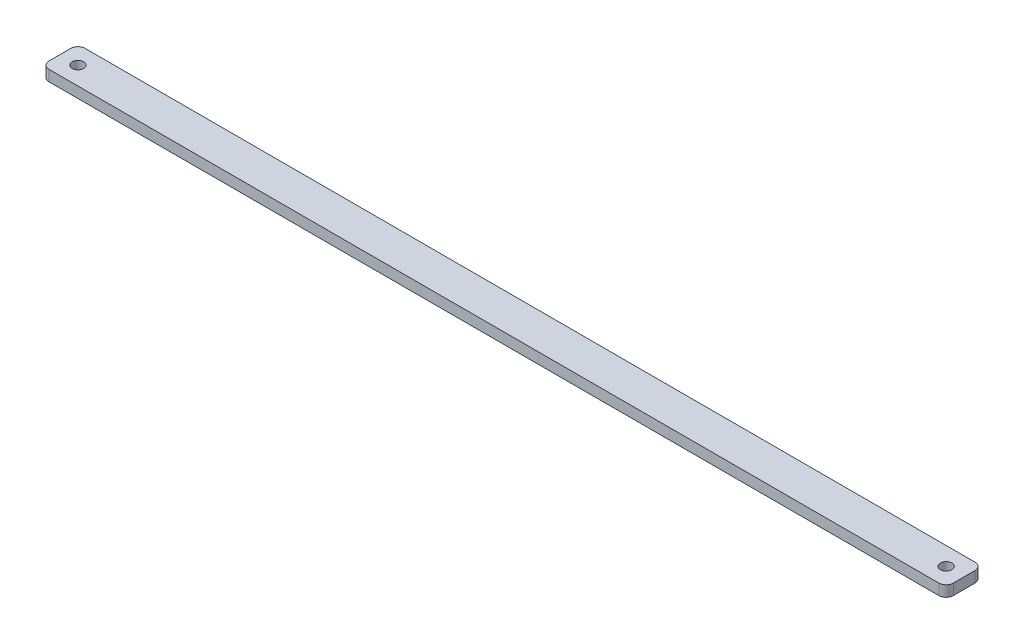
SolidWorks part; units mm, degrees
ref_plane "前视基准面" through (0, 0, 0) normal (0, 0, 1) x (1, 0, 0)
ref_plane "上视基准面" through (0, 0, 0) normal (0, 1, 0) x (1, 0, 0)
ref_plane "右视基准面" through (0, 0, 0) normal (1, 0, 0) x (0, 0, -1)
sketch "草图1" plane through (0, 0, 0) normal (0, 1, 0) x (1, 0, 0)
  line L0 (0, 0) -> (-50000, 0) construction
  line L1 (-125, 5) -> (125, 5)
  line L2 (-125, 5) -> (-125, -5)
  line L3 (-125, -5) -> (125, -5)
  line L4 (125, 5) -> (125, -5)
  line L5 (-125, 5) -> (125, -5) construction
  line L6 (-125, -5) -> (125, 5) construction
  line L7 (0, 0) -> (0, -50000) construction
  circle A0 centre (-120, 0) radius 1.6
  circle A1 centre (120, 0) radius 1.6
  point P0 (0, 0)
  point P8 (-120, 0)
  point P11 (120, 0)
  dimension "D4" = 3.2
  dimension "D5" = 3.2
  dimension "D1" = 250
  dimension "D2" = 10
  dimension "D3" = 240
extrude "凸台-拉伸1" add sketch "草图1" along normal blind 3
fillet "圆角2" radius 2 1 edges at (-125, 1.5, 5)
fillet "圆角3" radius 2 3 edges at (125, 1.5, 5) (125, 1.5, -5) (-125, 1.5, -5)
